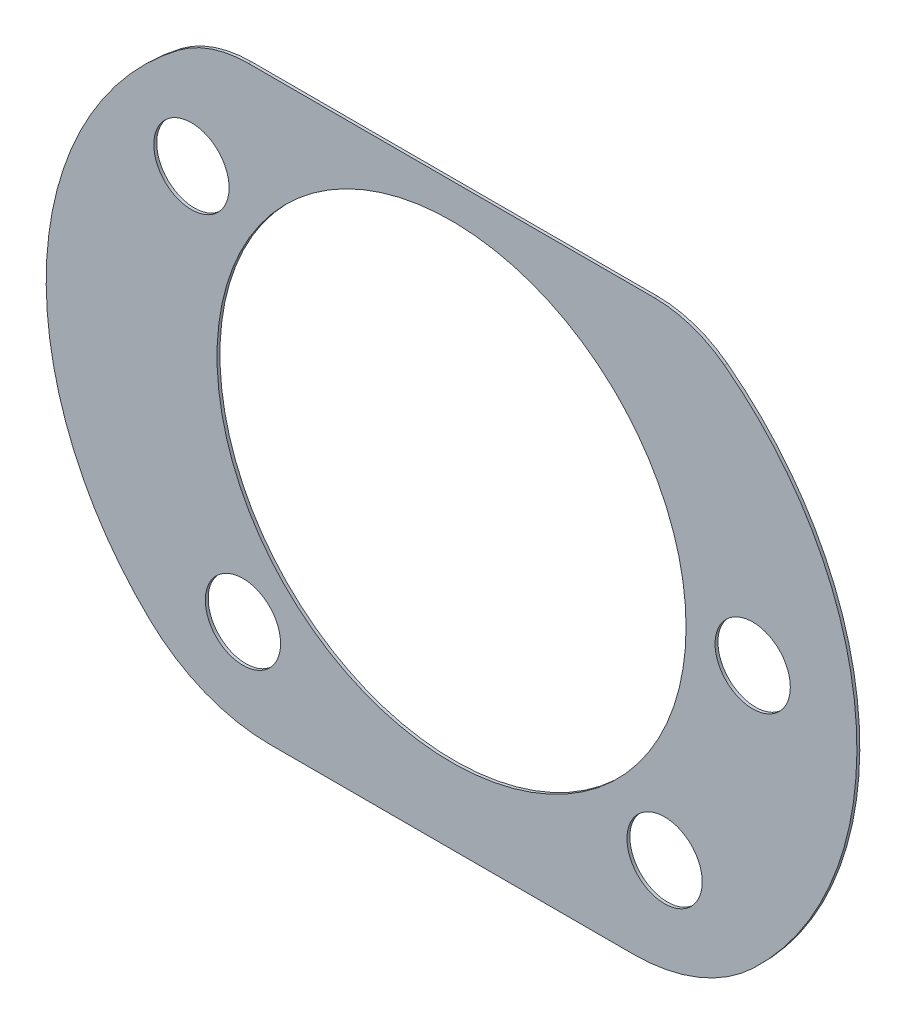
SolidWorks part; units mm, degrees
material "TESNIT BA-GL"
ref_plane "Front Plane" through (0, 0, 0) normal (0, 0, 1) x (1, 0, 0)
ref_plane "Top Plane" through (0, 0, 0) normal (0, 1, 0) x (1, 0, 0)
ref_plane "Right Plane" through (0, 0, 0) normal (1, 0, 0) x (0, 0, -1)
sketch "Sketch1" plane through (0, 0, 0) normal (0, 0, 1) x (1, 0, 0)
  line L0 (0, 0) -> (64.8791, 0) construction
  line L2 (-31.4198, -53.5) -> (31.4198, -53.5)
  line L3 (35.0661, 46.5) -> (-35.0661, 46.5)
  line L4 (0, 46.5) -> (0, -53.5) construction
  circle A0 centre (0, 0) radius 40.5
  circle A10 centre (-44.9173, 26.2) radius 6.5
  circle A11 centre (-36.0243, -37.5) radius 6.5
  circle A12 centre (36.7891, -36.75) radius 6.5
  circle A13 centre (52, 0) radius 6.5
  arc A14 (47.1226, 42.4574) -> (35.0661, 46.5) centre (35.0661, 26.5) ccw
  arc A15 (52.0937, -45.2391) -> (47.1226, 42.4574) centre (12.3998, -3.5) ccw
  arc A16 (31.4198, -53.5) -> (52.0937, -45.2391) centre (31.4198, -23.5) ccw
  arc A17 (-52.0931, -45.2397) -> (-31.4198, -53.5) centre (-31.4198, -23.5) ccw
  arc A18 (-47.1255, 42.4561) -> (-52.0931, -45.2397) centre (-12.4003, -3.4995) ccw
  arc A19 (-35.0661, 46.5) -> (-47.1255, 42.4561) centre (-35.0661, 26.4966) ccw
  dimension "D1" = 20
  dimension "D2" = 30
  dimension "D3" = 57.6
  dimension "D4" = 57.6
  dimension "D7" = 96.9173
  dimension "D8" = 8.893
  dimension "D9" = 81.7064
  dimension "D10" = 63.7
  dimension "D11" = 62.95
  dimension "D12" = 26.2
  dimension "D13" = 13
  dimension "D15" = 24.8001
  dimension "D18" = 81
  dimension "D5" = 100
  dimension "D6" = 44.9173
  dimension "D14" = 46.5
  dimension "D16" = 12.4003
  dimension "D17" = 3.5
extrude "Extrude1" add sketch "Sketch1" along normal blind 0.5
